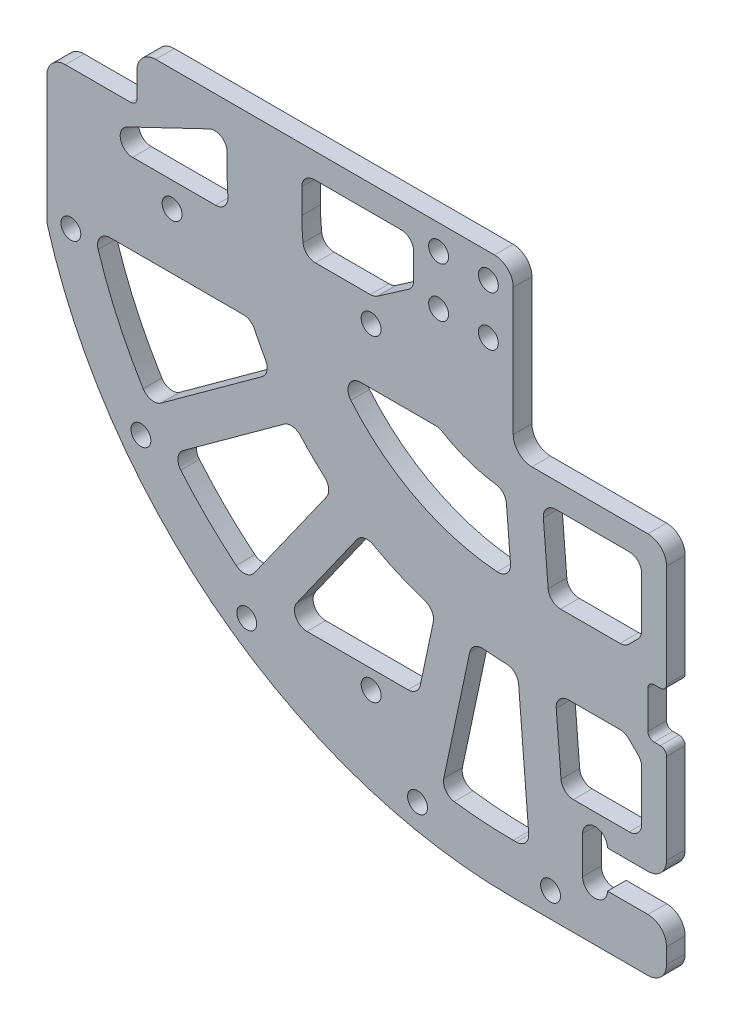
SolidWorks part; units mm, degrees
material "A-玻璃纤维"
ref_plane "前视基准面" through (0, 0, 0) normal (0, 0, 1) x (1, 0, 0)
ref_plane "上视基准面" through (0, 0, 0) normal (0, 1, 0) x (1, 0, 0)
ref_plane "右视基准面" through (0, 0, 0) normal (1, 0, 0) x (0, 0, -1)
sketch "草图1" plane through (0, 0, 0) normal (0, 0, 1) x (1, 0, 0)
  line L0 (-139.1546, 76.5) -> (-139.1546, -33.6254) construction
  line L1 (-91.6495, 50) -> (0, 50) construction
  line L2 (-90.2793, 53) -> (-5.3283, 53) construction
  line L4 (-99.1546, 26.5) -> (0, 26.5) construction
  line L6 (-99.1546, 26.5) -> (-88, 26.5) construction
  line L7 (0, 26.5) -> (0, 0) construction
  line L8 (-88, 26.5) -> (-88, -20.8435) construction
  arc A0 (-139.1546, 66.5) -> (-99.1546, 26.5) centre (-99.1546, 66.5) ccw
  dimension "D1" = 3
  dimension "D4" = 80
  dimension "D3" = 23.5
  dimension "D7" = 10
  dimension "D8" = 88
  dimension "D9" = 11.1546
sketch "草图2" plane through (0, 0, 0) normal (0, 0, 1) x (1, 0, 0)
  line L0 (0, 0) -> (-88, 0) construction
  line L1 (-88, 26.5) -> (-88, -20.8435) construction
  line L2 (0, 3) -> (-88, 3) construction
  line L3 (-99.1546, 26.5) -> (0, 26.5) construction
  line L4 (-139.1546, 76.5) -> (-139.1546, -33.6254) construction
  line L5 (-99.1546, 26.5) -> (-88, 26.5) construction
  line L6 (-139.1546, 76.5) -> (-139.1546, 66.5) construction
  line L7 (-88, 3) -> (-88, 26.5) construction
  line L8 (-161.1546, 76.5) -> (-161.1546, 66.5) construction
  line L9 (-99.1546, 4.5) -> (-88, 4.5) construction
  line L10 (-117.1546, 76.5) -> (-117.1546, 66.5) construction
  line L11 (-99.1546, 48.5) -> (-88, 48.5) construction
  line L12 (-70.5, 3) -> (-70.5, 50) construction
  line L13 (-162.1546, 76.5) -> (-162.1546, 66.5) construction
  line L14 (-99.1546, 3.5) -> (-88, 3.5) construction
  line L15 (-164.6546, 76.5) -> (-164.6546, 66.5) construction
  line L16 (-99.1546, 1) -> (-88, 1) construction
  line L17 (-169.1546, 76.5) -> (-169.1546, 66.5) construction
  line L18 (-99.1546, -3.5) -> (-88, -3.5) construction
  line L19 (-177.1546, 76.5) -> (-177.1546, 66.5)
  line L20 (-99.1546, -11.5) -> (-88, -11.5)
  line L21 (-177.1546, 76.5) -> (-162.1546, 76.5) construction
  line L22 (-88, 3.5) -> (-88, -11.5) construction
  line L23 (-99.1546, 66.5) -> (-99.1546, 1) construction
  line L24 (-99.1546, 66.5) -> (-106.9101, 1.4608) construction
  line L25 (-164.6546, 75.2931) -> (-164.6546, 78.7931) construction
  line L26 (-91.6495, 50) -> (0, 50) construction
  line L27 (0, -3) -> (-88, -3) construction
  line L28 (-74.5, 50) -> (-74.5, 29.5)
  line L29 (-74.5, 29.5) -> (-77.5, 29.5)
  line L30 (-77.5, 29.5) -> (-77.5, 21.5)
  line L31 (-77.5, 21.5) -> (-74.5, 21.5)
  line L32 (-74.5, 21.5) -> (-74.5, 3)
  line L33 (-74.5, 3) -> (-88, 3)
  line L34 (-88, 3) -> (-88, -3)
  line L35 (-88, -3) -> (-74.5, -3)
  line L36 (-74.5, -3) -> (-74.5, -11.5)
  line L37 (-74.5, -11.5) -> (-88, -11.5)
  line L38 (-177.1546, 76.5) -> (-99.1546, 76.5)
  line L39 (-99.1546, 76.5) -> (-99.1546, 50)
  line L40 (-99.1546, 50) -> (-74.5, 50)
  line L41 (-72.5, 50) -> (-72.5, 27.5) construction
  line L42 (-72.5, 27.5) -> (-75.5, 27.5) construction
  line L43 (-75.5, 27.5) -> (-75.5, 23.5) construction
  line L44 (-75.5, 23.5) -> (-72.5, 23.5) construction
  line L45 (-72.5, 23.5) -> (-72.5, 3) construction
  arc A0 (-139.1546, 66.5) -> (-99.1546, 26.5) centre (-99.1546, 66.5) ccw construction
  arc A1 (-139.1546, 66.5) -> (-99.1546, 26.5) centre (-99.1546, 66.5) ccw construction
  arc A2 (-161.1546, 66.5) -> (-99.1546, 4.5) centre (-99.1546, 66.5) ccw construction
  arc A3 (-117.1546, 66.5) -> (-99.1546, 48.5) centre (-99.1546, 66.5) ccw construction
  arc A4 (-162.1546, 66.5) -> (-99.1546, 3.5) centre (-99.1546, 66.5) ccw construction
  arc A5 (-164.6546, 66.5) -> (-99.1546, 1) centre (-99.1546, 66.5) ccw construction
  arc A6 (-169.1546, 66.5) -> (-99.1546, -3.5) centre (-99.1546, 66.5) ccw construction
  arc A7 (-177.1546, 66.5) -> (-99.1546, -11.5) centre (-99.1546, 66.5) ccw
  circle A8 centre (-91.7546, 1) radius 3.5 construction
  circle A9 centre (-99.1546, 1) radius 3.5 construction
  circle A10 centre (-106.9101, 1.4608) radius 3.5 construction
  circle A11 centre (-114.5564, 2.8366) radius 3.5 construction
  circle A12 centre (-121.9861, 5.108) radius 3.5 construction
  circle A13 centre (-129.0945, 8.2432) radius 3.5 construction
  circle A14 centre (-135.7817, 12.198) radius 3.5 construction
  circle A15 centre (-141.9536, 16.9168) radius 3.5 construction
  circle A16 centre (-147.5234, 22.3332) radius 3.5 construction
  circle A17 centre (-152.4127, 28.3709) radius 3.5 construction
  circle A18 centre (-156.5527, 34.9451) radius 3.5 construction
  circle A19 centre (-159.8851, 41.9633) radius 3.5 construction
  circle A20 centre (-162.3632, 49.3266) radius 3.5 construction
  circle A21 centre (-163.9519, 56.9316) radius 3.5 construction
  circle A22 centre (-164.6291, 64.6711) radius 3.5 construction
  circle A23 centre (-164.6546, 72.3711) radius 3.5 construction
  arc A24 (-139.1546, 66.5) -> (-99.1546, 26.5) centre (-99.1546, 66.5) ccw construction
  dimension "D8" = 7
  dimension "D9" = 7
  dimension "D10" = 7.4
  dimension "D13" = 7
  dimension "D16" = 17.5
  dimension "D1" = 3
  dimension "D2" = 22
  dimension "D4" = 1
  dimension "D12" = 6.8
  dimension "D14" = 7.7691
  dimension "D15" = 7.7
  dimension "D17" = 3
  dimension "D18" = 2
  dimension "D19" = 4
  dimension "D20" = 20.5
  dimension "D21" = 5
  dimension "D22" = 8
  dimension "D23" = 4
  dimension "D24" = 7
  dimension "D25" = 2
  dimension "D3" = 22
  dimension "D5" = 3.5
  dimension "D6" = 7
  dimension "D7" = 8
  dimension "D11" = 14
extrude "凸台-拉伸1" add sketch "草图2" along normal blind 3 contours L38 L39 L40 L28 L29 L30 L31 L32 L33 L34 L35 L36 L37 L20 A7 L19
sketch "草图3" plane through (0, 0, 3) normal (0, 0, 1) x (1, 0, 0)
  line L0 (-74.5, 3) -> (-88, 3) construction
  line L1 (-88, -3) -> (-74.5, -3) construction
  circle A0 centre (-86, 3) radius 2
  circle A1 centre (-86, -3) radius 2
  dimension "D1" = 4
  dimension "D2" = 4
extrude "切除-拉伸1" cut sketch "草图3" against normal blind 3
sketch "草图5" plane through (0, 0, 3) normal (0, 0, 1) x (1, 0, 0)
  line L0 (-182.4463, 78.5) -> (-171.1339, 78.5) construction
  line L1 (-192.9816, 70) -> (-179.5561, 70) construction
  line L2 (-177.1546, 76.5) -> (-99.1546, 76.5) construction
  line L3 (-177.1546, 68.5) -> (-159.6546, 68.5)
  line L4 (-177.1546, 76.5) -> (-177.1546, 66.5) construction
  line L5 (-159.6546, 68.5) -> (-159.6546, 76.5)
  line L6 (-159.6546, 76.5) -> (-177.1546, 76.5)
  line L7 (-177.1546, 76.5) -> (-177.1546, 68.5)
  dimension "D1" = 2
  dimension "D2" = 8.5
  dimension "D3" = 17.5
  dimension "D4" = 1.5
extrude "切除-拉伸2" cut sketch "草图5" against normal blind 3
fillet "圆角1" radius 1 1 edges at (-159.6546, 68.5, 1.5)
fillet "圆角2" radius 1 4 edges at (-74.5, 21.5, 1.5) (-77.5, 21.5, 1.5) (-77.5, 29.5, 1.5) (-74.5, 29.5, 1.5)
sketch "草图6" plane through (0, 0, 3) normal (0, 0, 1) x (1, 0, 0)
  line L0 (-174.1546, 69.5027) -> (-174.1546, 33.4707)
  line L1 (-174.1546, 33.4707) -> (-188.349, 74.6409)
  line L2 (-188.349, 74.6409) -> (-174.1546, 69.5027)
  line L3 (-177.1546, 68.5) -> (-177.1546, 66.5) construction
  dimension "D1" = 3
extrude "切除-拉伸3" cut sketch "草图6" against normal blind 10
sketch "草图7" plane through (0, 0, 3) normal (0, 0, 1) x (1, 0, 0)
  line L0 (-84, 3) -> (-172.2493, 3) construction
  line L1 (-137, 6) -> (-142, 6) construction
  line L2 (-117, 9) -> (-157, 9) construction
  line L3 (-117, 9) -> (-117, 3) construction
  line L4 (-117, 3) -> (-157, 3) construction
  line L5 (-157, 9) -> (-157, 3) construction
  line L6 (-117, 9) -> (-157, 3) construction
  line L7 (-117, 3) -> (-157, 9) construction
  line L8 (-137, 6) -> (-122, 6) construction
  circle A0 centre (-122, 6) radius 1.6
  circle A1 centre (-142, 6) radius 1.6
  arc A2 (-174.1546, 45.0757) -> (-99.1546, -11.5) centre (-99.1546, 66.5) ccw construction
  arc A3 (-174.1546, 45.0757) -> (-99.1546, -11.5) centre (-99.1546, 66.5) ccw construction
  arc A4 (-170.3084, 46.1744) -> (-99.1546, -7.5) centre (-99.1546, 66.5) ccw construction
  point P3 (-137, 6)
  dimension "D5" = 15
  dimension "D6" = 3.2
  dimension "D7" = 3.2
  dimension "D1" = 6
  dimension "D2" = 40
  dimension "D3" = 157
  dimension "D4" = 5
  dimension "D8" = 4
extrude "切除-拉伸4" cut sketch "草图7" against normal blind 10
sketch "草图8" plane through (0, 0, 3) normal (0, 0, 1) x (1, 0, 0)
  line L0 (-99.1546, -11.5) -> (-74.5, -11.5) construction
  line L1 (-99.1546, -11.5) -> (-74.5, -11.5) construction
  line L2 (-99.1546, -7.5) -> (-74.5, -7.5) construction
  line L3 (-99.1546, 66.5) -> (-170.288, 46.1028) construction
  line L4 (-99.1546, 66.5) -> (-189.9875, 66.5) construction
  line L5 (-99.1546, 66.5) -> (-159.0218, 23.0039) construction
  line L6 (-142, 6) -> (-99.1546, 66.5) construction
  line L7 (-99.1546, 66.5) -> (-99.1546, -7.5) construction
  line L8 (-84, -3) -> (-148.0361, -3) construction
  line L10 (-99.1546, 66.5) -> (-114.5401, -5.8829) construction
  arc A0 (-174.1546, 45.0757) -> (-99.1546, -11.5) centre (-99.1546, 66.5) ccw construction
  arc A1 (-174.1546, 45.0757) -> (-99.1546, -11.5) centre (-99.1546, 66.5) ccw construction
  arc A2 (-170.3084, 46.1744) -> (-99.1546, -7.5) centre (-99.1546, 66.5) ccw construction
  circle A3 centre (-170.288, 46.1028) radius 1.6
  circle A4 centre (-159.0218, 23.0039) radius 1.6
  circle A6 centre (-93.1546, -7.5) radius 1.6
  circle A7 centre (-114.5401, -5.8829) radius 1.6
  circle A8 centre (-114.5401, -5.8829) radius 2 construction
  circle A9 centre (-114.5401, -5.8829) radius 3 construction
  dimension "D2" = 3.2
  dimension "D4" = 20
  dimension "D6" = 3.2
  dimension "D7" = 6
  dimension "D8" = 3.2
  dimension "D9" = 6
  dimension "D10" = 3.2
  dimension "D11" = 4
  dimension "D13" = 74
  dimension "D3" = 16
  dimension "D5" = 38.694
  dimension "D12" = 12
extrude "切除-拉伸5" cut sketch "草图8" against normal blind 10
sketch "草图9" plane through (0, 0, 3) normal (0, 0, 1) x (1, 0, 0)
  line L0 (-159.6546, 76.5) -> (-99.1546, 76.5) construction
  line L1 (-99.1546, 76.5) -> (-99.1546, 50) construction
  circle A0 centre (-103.1546, 72.5) radius 1.6
  circle A1 centre (-111.1546, 72.5) radius 1.6
  circle A2 centre (-111.1546, 64.5) radius 1.6
  circle A3 centre (-103.1546, 64.5) radius 1.6
  dimension "D1" = 3.2
  dimension "D2" = 4
  dimension "D3" = 4
  dimension "D6" = 8
  dimension "D7" = 8
  dimension "D4" = 2
  dimension "D5" = 2
extrude "切除-拉伸6" cut sketch "草图9" against normal blind 3
sketch "草图10" plane through (0, 0, 3) normal (0, 0, 1) x (1, 0, 0)
  line L0 (-99.1546, 50) -> (-159.4805, 50) construction
  line L1 (-154.0101, 57) -> (-122.0101, 57) construction
  line L2 (-138.0101, 57) -> (-138.0101, 65.9005) construction
  arc A0 (-139.1546, 66.5) -> (-99.1546, 26.5) centre (-99.1546, 66.5) ccw construction
  circle A1 centre (-122.0101, 57) radius 1.6
  circle A2 centre (-154.0101, 57) radius 1.6
  dimension "D2" = 3.2
  dimension "D3" = 3.2
  dimension "D1" = 7
  dimension "D4" = 32
extrude "切除-拉伸7" cut sketch "草图10" against normal blind 3
sketch "草图11" plane through (0, 0, 3) normal (0, 0, 1) x (1, 0, 0)
  line L0 (-122.0101, 57) -> (-114.0101, 57) construction
  line L1 (-114.0101, 57) -> (-114.0101, 61) construction
  line L2 (-114.0101, 61) -> (-122.0101, 61) construction
  dimension "D1" = 8
  dimension "D2" = 4
fillet "圆角3" radius 3 1 edges at (-99.1546, 50, 1.5)
fillet "圆角4" radius 3 8 edges at (-174.1546, 68.5, 1.5) (-159.6546, 76.5, 1.5) (-99.1546, 76.5, 1.5) (-74.5, 50, 1.5) (-74.5, 3, 1.5) (-74.5, -3, 1.5) (-74.5, -11.5, 1.5) (-174.1546, 45.0757, 1.5)
sketch "草图13" plane through (0, 0, 3) normal (0, 0, 1) x (1, 0, 0)
  line L0 (-99.1546, 26.5) -> (0, 26.5) construction
  line L1 (-139.1546, 76.5) -> (-139.1546, 66.5) construction
  line L3 (-99.1546, 20.5) -> (-98.4347, 20.5)
  line L4 (-133.1546, 72.5) -> (-133.1546, 66.5)
  line L5 (-101.7131, 60.933) -> (-101.3333, 56.2498)
  line L7 (-166.6657, 48) -> (-141.2705, 48)
  line L8 (-133.1546, 72.5) -> (-115.1546, 72.5)
  line L9 (-115.1546, 72.5) -> (-115.1546, 65.3828)
  line L10 (-115.1546, 65.3828) -> (-121.4982, 61)
  line L11 (-122.0101, 57) -> (-111.1546, 64.5) construction
  line L14 (-132.7068, 61) -> (-121.4982, 61)
  line L15 (-99.1546, 66.5) -> (-159.0218, 23.0039) construction
  line L16 (-99.1546, 66.5) -> (-142, 6) construction
  line L17 (-101.6028, 68.2338) -> (-112.1362, 53.3601)
  line L18 (-99.1546, 66.5) -> (-114.5401, -5.8829) construction
  line L19 (-99.1546, 66.5) -> (-93.1546, -7.5) construction
  line L20 (-102.089, 67.1237) -> (-105.1135, 52.8949)
  line L21 (-102.1448, 66.2576) -> (-101.3333, 56.2498)
  line L22 (-101.7131, 60.933) -> (-112.1362, 53.3601)
  line L23 (-96.7063, 64.7662) -> (-105.1135, 52.8949)
  line L24 (-96.2201, 65.8763) -> (-98.3077, 56.0551)
  line L25 (-127.6809, 48) -> (-111.0605, 48)
  line L26 (-97.3912, 64.0729) -> (-112.1362, 53.3601)
  line L27 (-99.1546, -3.5) -> (-96.4888, -3.5)
  line L28 (-136.1993, 9) -> (-114.4436, 9)
  line L29 (-138.0535, 41.9465) -> (-157.4971, 27.8199)
  line L30 (-134.5268, 37.0924) -> (-153.9704, 22.9658)
  line L31 (-128.1314, 30.774) -> (-142.0214, 11.1607)
  line L32 (-123.2349, 27.3064) -> (-136.1993, 9)
  line L33 (-111.6326, 22.2247) -> (-114.4436, 9)
  line L34 (-105.7637, 20.9773) -> (-110.7606, -2.5312)
  line L35 (-98.4347, 20.5) -> (-96.4888, -3.5)
  line L39 (-100.3834, 44.5343) -> (-99.4078, 32.5009)
  arc A0 (-139.1546, 66.5) -> (-99.1546, 26.5) centre (-99.1546, 66.5) ccw construction
  arc A2 (-133.1546, 66.5) -> (-132.7068, 61) centre (-99.1546, 66.5) ccw
  arc A3 (-111.0605, 48) -> (-100.3834, 44.5343) centre (-99.1546, 66.5) ccw
  arc A4 (-141.2705, 48) -> (-138.0535, 41.9465) centre (-99.1546, 66.5) ccw
  arc A5 (-166.6657, 48) -> (-157.4971, 27.8199) centre (-99.1546, 66.5) ccw
  arc A6 (-153.9704, 22.9658) -> (-142.0214, 11.1607) centre (-99.1546, 66.5) ccw
  arc A7 (-134.5268, 37.0924) -> (-128.1314, 30.774) centre (-99.1546, 66.5) ccw
  arc A8 (-110.7606, -2.5312) -> (-99.1546, -3.5) centre (-99.1546, 66.5) ccw
  arc A9 (-123.2349, 27.3064) -> (-111.6326, 22.2247) centre (-99.1546, 66.5) ccw
  arc A10 (-105.7637, 20.9773) -> (-99.1546, 20.5) centre (-99.1546, 66.5) ccw
  arc A11 (-127.6809, 48) -> (-99.4078, 32.5009) centre (-99.1546, 66.5) ccw
extrude "切除-拉伸8" cut sketch "草图13" against normal blind 11.6 contours L7 A5 L29 A4 | A7 L30 A6 L31 | L25 A11 L39 A3 | L4 A2 L14 L10 L9 L8 | A9 L32 L28 L33 | A10 L34 A8 L27 L35 L3
sketch "草图14" plane through (0, 0, 3) normal (0, 0, 1) x (1, 0, 0)
  line L0 (-133.1546, 72.5) -> (-133.1546, 66.5) construction
  line L1 (-133.1546, 72.5) -> (-133.1546, 66.5) construction
  line L2 (-145.1546, 72.5) -> (-145.1546, 66.5)
  line L3 (-144.8246, 61) -> (-169.1546, 61)
  line L4 (-169.1546, 61) -> (-145.1546, 72.5)
  line L5 (-174.1546, 45.5) -> (-174.1546, 65.5) construction
  line L6 (-145.1546, 72.5) -> (-133.1546, 72.5) construction
  line L7 (-99.1546, 66.5) -> (-93.1546, -7.5) construction
  line L8 (-94.4826, 46) -> (-93.388, 32.5)
  line L9 (-94.4826, 46) -> (-78.5, 46)
  line L10 (-78.5, 46) -> (-78.5, 35.1546)
  line L11 (-81.1546, 32.5) -> (-93.388, 32.5)
  line L12 (-92.415, 20.5) -> (-81.1546, 20.5)
  line L13 (-78.5, 17.8454) -> (-78.5, 7)
  line L14 (-78.5, 7) -> (-91.3204, 7)
  line L15 (-77.5, 3) -> (-84, 3) construction
  line L16 (-99.1546, 26.5) -> (0, 26.5) construction
  line L17 (-74.5, 20.5) -> (-74.5, 6) construction
  line L19 (-91.6495, 50) -> (0, 50) construction
  line L20 (-96.1644, 66.7424) -> (-90.1644, -7.2576) construction
  line L21 (-92.415, 20.5) -> (-91.3204, 7)
  line L22 (-78.5, 35.1546) -> (-81.1546, 32.5)
  line L23 (-88, 26.5) -> (-76.1865, 26.5) construction
  line L24 (-78.5, 17.8454) -> (-81.1546, 20.5)
  arc A0 (-133.1546, 66.5) -> (-132.7068, 61) centre (-99.1546, 66.5) ccw construction
  arc A1 (-133.1546, 66.5) -> (-132.7068, 61) centre (-99.1546, 66.5) ccw construction
  arc A2 (-145.1546, 66.5) -> (-144.8246, 61) centre (-99.1546, 66.5) ccw
  arc A3 (-145.1546, 66.5) -> (-144.5487, 59.0588) centre (-99.1546, 66.5) ccw construction
  dimension "D1" = 12
  dimension "D2" = 5
  dimension "D3" = 3
  dimension "D4" = 4
  dimension "D5" = 6
  dimension "D6" = 4
  dimension "D9" = 4
  dimension "D10" = 135
  dimension "D11" = 18
extrude "切除-拉伸9" cut sketch "草图14" against normal blind 11.6
fillet "圆角5" radius 2 38 edges at (-111.6326, 22.2247, 1.5) (-114.4436, 9, 1.5) (-136.1993, 9, 1.5) (-123.2349, 27.3064, 1.5) (-115.1546, 72.5, 1.5) (-115.1546, 65.3828, 1.5) (-121.4982, 61, 1.5) (-132.7068, 61, 1.5) (-133.1546, 72.5, 1.5) (-128.1314, 30.774, 1.5) (-142.0214, 11.1607, 1.5) (-153.9704, 22.9658, 1.5) (-134.5268, 37.0924, 1.5) (-138.0535, 41.9465, 1.5) (-157.4971, 27.8199, 1.5) (-166.6657, 48, 1.5) (-98.4347, 20.5, 1.5) (-96.4888, -3.5, 1.5) (-110.7606, -2.5312, 1.5) (-105.7637, 20.9773, 1.5) (-111.0605, 48, 1.5) (-100.3834, 44.5343, 1.5) (-99.4078, 32.5009, 1.5) (-127.6809, 48, 1.5) (-81.1546, 20.5, 1.5) (-78.5, 17.8454, 1.5) (-78.5, 7, 1.5) (-91.3204, 7, 1.5) (-92.415, 20.5, 1.5) (-78.5, 35.1546, 1.5) (-81.1546, 32.5, 1.5) (-93.388, 32.5, 1.5) (-94.4826, 46, 1.5) (-78.5, 46, 1.5) (-144.8246, 61, 1.5) (-169.1546, 61, 1.5) (-145.1546, 72.5, 1.5) (-141.2705, 48, 1.5)
